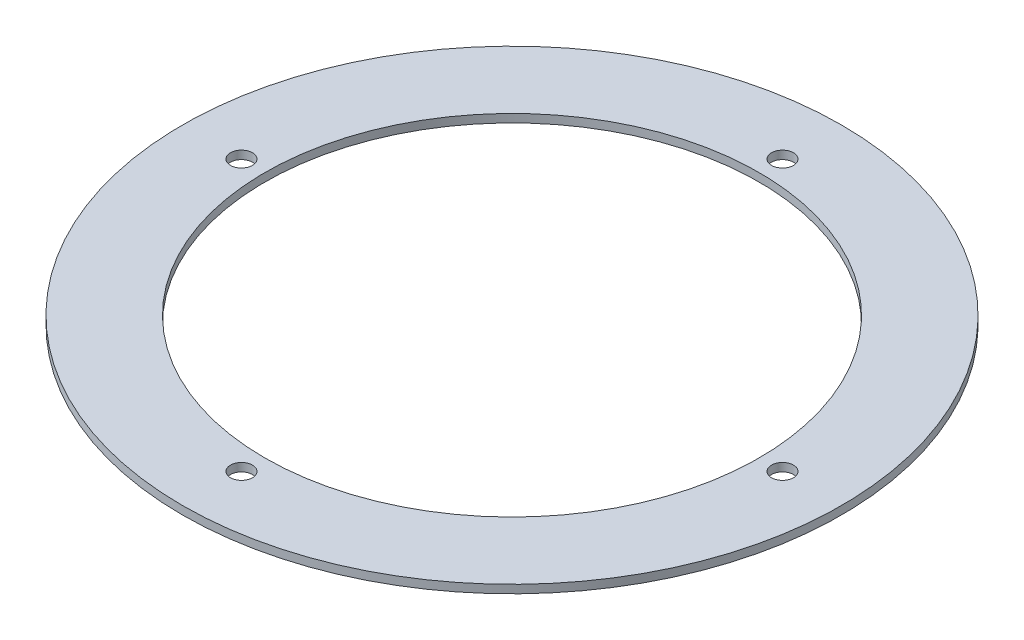
SolidWorks part; units mm, degrees
ref_plane "Front Plane" through (0, 0, 0) normal (0, 0, 1) x (1, 0, 0)
ref_plane "Top Plane" through (0, 0, 0) normal (0, 1, 0) x (1, 0, 0)
ref_plane "Right Plane" through (0, 0, 0) normal (1, 0, 0) x (0, 0, -1)
sketch "Sketch1" plane through (0, 0, 0) normal (0, 1, 0) x (1, 0, 0)
  line L0 (0, 60) -> (0, -60) construction
  line L1 (-60, 0) -> (60, 0) construction
  circle A0 centre (0, 0) radius 60
  circle A1 centre (0, 0) radius 45
  circle A2 centre (0, 0) radius 49.25 construction
  circle A6 centre (-49.25, 0) radius 2
  circle A7 centre (0, 49.25) radius 2
  circle A8 centre (49.25, 0) radius 2
  circle A9 centre (0, -49.25) radius 2
  point P20 (0, 0)
  dimension "D1" = 90
  dimension "D2" = 49.25
  dimension "D3" = 4
extrude "Boss-Extrude1" add sketch "Sketch1" along normal blind 1.5
